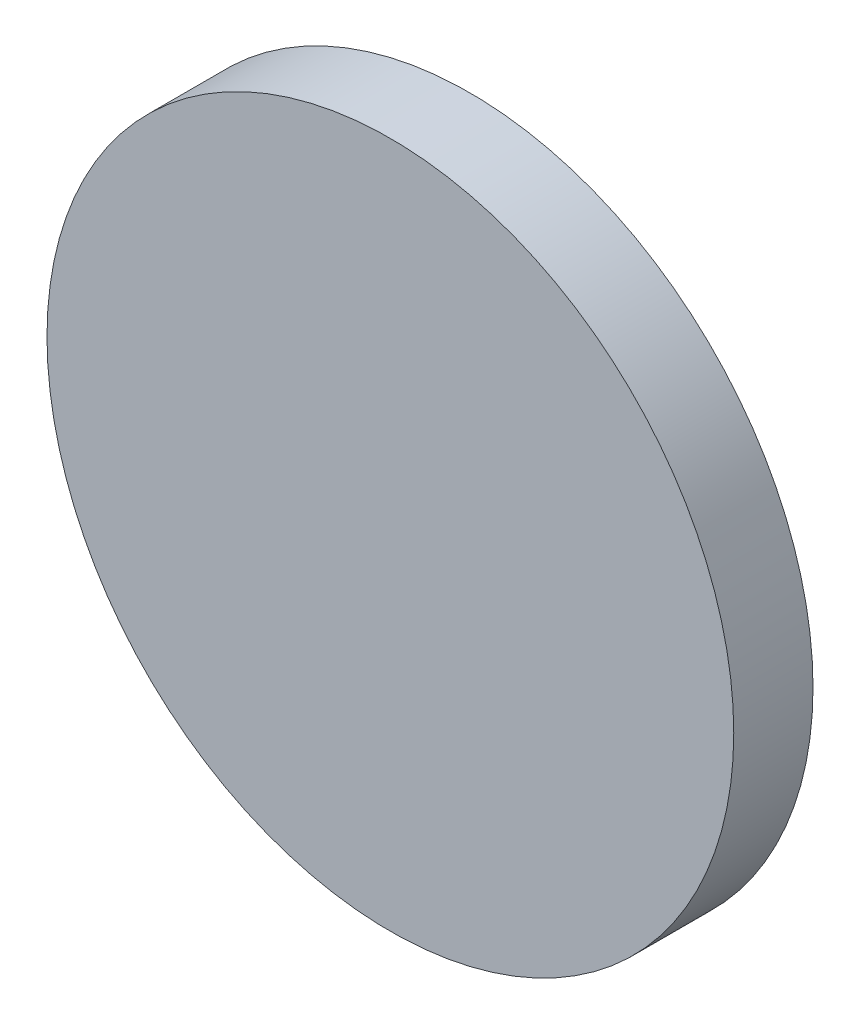
SolidWorks part; units mm, degrees
ref_plane "Front Plane" through (0, 0, 0) normal (0, 0, 1) x (1, 0, 0)
ref_plane "Top Plane" through (0, 0, 0) normal (0, 1, 0) x (1, 0, 0)
ref_plane "Right Plane" through (0, 0, 0) normal (1, 0, 0) x (0, 0, -1)
sketch "Sketch1" plane through (0, 0, 0) normal (0, 0, 1) x (1, 0, 0)
  circle A0 centre (0, 0) radius 41.275
  dimension "D1" = 82.55
extrude "Boss-Extrude1" add sketch "Sketch1" along normal blind 9.525
